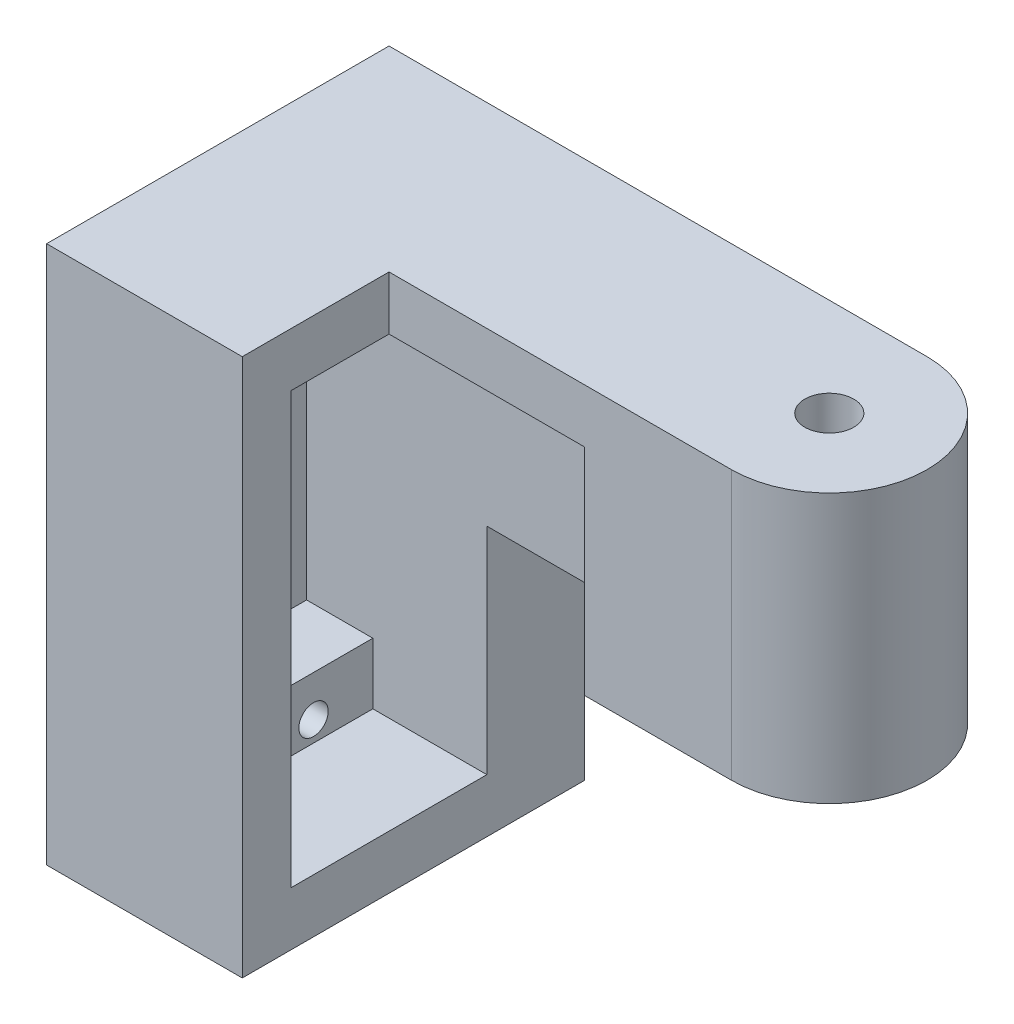
SolidWorks part; units mm, degrees
ref_plane "Front Plane" through (0, 0, 0) normal (0, 0, 1) x (1, 0, 0)
ref_plane "Top Plane" through (0, 0, 0) normal (0, 1, 0) x (1, 0, 0)
ref_plane "Right Plane" through (0, 0, 0) normal (1, 0, 0) x (0, 0, -1)
sketch "Sketch1" plane through (0, 0, 0) normal (0, 0, 1) x (1, 0, 0)
  line L1 (-76.2, -19.05) -> (76.2, -19.05)
  line L2 (-76.2, -19.05) -> (-76.2, 19.05)
  line L3 (-76.2, 19.05) -> (76.2, 19.05)
  line L4 (76.2, -19.05) -> (76.2, 19.05)
  line L5 (-76.2, -19.05) -> (76.2, 19.05) construction
  line L6 (-76.2, 19.05) -> (76.2, -19.05) construction
  circle A1 centre (76.2, 0) radius 19.05
  point P0 (0, 0)
  dimension "D1" = 38.1
  dimension "D2" = 152.4
extrude "Boss-Extrude1" add sketch "Sketch1" along normal blind 25.4
sketch "Sketch4" plane through (0, 0, 25.4) normal (0, 0, 1) x (1, 0, 0)
  line L1 (-76.2, 45.72) -> (-50.8, 45.72)
  line L2 (-76.2, 45.72) -> (-76.2, -24.13)
  line L3 (-76.2, -24.13) -> (-50.8, -24.13)
  line L4 (-50.8, 45.72) -> (-50.8, -24.13)
  line L5 (-76.2, 0) -> (95.25, 0) construction
  line L6 (-76.2, -19.05) -> (-76.2, 19.05) construction
  line L8 (-76.2, -19.05) -> (76.2, -19.05) construction
  arc A0 (76.2, -19.05) -> (76.2, 19.05) centre (76.2, 0) ccw construction
  point P10 (-71.4875, 31.0279)
  point P13 (-76.2, -21.835)
  dimension "D1" = 25.4
  dimension "D2" = 69.85
  dimension "D3" = 5.08
extrude "Boss-Extrude3" add sketch "Sketch4" along normal blind 19.05 and the other way up to surface other way up to face at (4.7625, 0, 0)
sketch "Sketch5" plane through (-76.2, 0, 0) normal (-1, 0, 0) x (0, 0, 1)
  line L0 (32.385, 0) -> (18.415, 0) construction
  line L1 (30.4, 34.4998) -> (20.4, 34.4998) construction
  line L2 (30.4, -14.5001) -> (20.4, -14.5001) construction
  line L3 (25.4, 6.985) -> (25.4, -6.985) construction
  line L10 (25.4, -19.05) -> (25.4, 19.05) construction
  circle A0 centre (25.4, 0) radius 6.985
  circle A1 centre (30.4, -14.5001) radius 1.905
  circle A2 centre (30.4, 34.4998) radius 1.905
  circle A3 centre (20.4, 34.4998) radius 1.905
  circle A4 centre (20.4, -14.5001) radius 1.905
  point P2 (36.4462, -5.8241)
  point P3 (30.6052, -14.5696)
  point P4 (32.385, 0)
  point P19 (25.4, 0)
  dimension "D1" = 13.97
  dimension "D2" = 3.81
  dimension "D3" = 48.9999
  dimension "D4" = 14.5001
  dimension "D5" = 10
extrude "Cut-Extrude1" cut sketch "Sketch5" against normal up to surface (25.4 mm away) up to face at (-50.8, 5.3975, 17.4625)
sketch "Sketch13" plane through (0, 0, 25.4) normal (0, 0, 1) x (1, 0, 0)
  line L0 (-76.2, -24.13) -> (-50.8, -24.13) construction
  line L1 (-50.8, 45.72) -> (12.7, 45.72)
  line L2 (-50.8, 45.72) -> (-50.8, -24.13)
  line L3 (-50.8, -24.13) -> (12.7, -24.13)
  line L4 (12.7, 45.72) -> (12.7, -24.13)
  dimension "D1" = 63.5
extrude "Boss-Extrude6" add sketch "Sketch13" against normal up to surface (25.4 mm away) up to face at (-23.0188, 5.3975, 0)
sketch "Sketch7" plane through (0, 0, 25.4) normal (0, 0, 1) x (1, 0, 0)
  line L0 (-50.8, -24.13) -> (12.7, -24.13) construction
  line L2 (-50.8, 6.985) -> (-50.8, 45.72) construction
  line L3 (0, -17.145) -> (-50.8, -17.145)
  line L4 (0, -17.145) -> (0, 38.735)
  line L5 (0, 38.735) -> (-50.8, 38.735)
  line L6 (-50.8, -17.145) -> (-50.8, 38.735)
  line L7 (0, -17.145) -> (-50.8, 38.735) construction
  line L8 (0, 38.735) -> (-50.8, -17.145) construction
  line L9 (0, -17.145) -> (0, -24.13) construction
  line L12 (0, 38.735) -> (0, 45.72) construction
  line L15 (12.7, 45.72) -> (-50.8, 45.72) construction
  point P0 (0, -21.59)
  point P2 (0, 41.91)
  point P5 (-25.4, 10.795)
  point P15 (0, -41.91)
  dimension "D1" = 55.88
  dimension "D2" = 50.8
extrude "Cut-Extrude2" cut sketch "Sketch7" against normal up to surface (25.4 mm away) up to face at (8.7312, 5.3975, 0)
sketch "Sketch8" plane through (-50.8, 0, 0) normal (1, 0, 0) x (0, 0, -1)
  line L1 (-38.1, -9.205) -> (-12.7, -9.205)
  line L2 (-38.1, -9.205) -> (-38.1, 30.795)
  line L3 (-38.1, 30.795) -> (-12.7, 30.795)
  line L4 (-12.7, -9.205) -> (-12.7, 30.795)
  line L5 (-38.1, -9.205) -> (-12.7, 30.795) construction
  line L6 (-38.1, 30.795) -> (-12.7, -9.205) construction
  line L11 (-25.4, 30.795) -> (-25.4, -9.205) construction
  line L12 (-25.4, -24.13) -> (-25.4, -17.145) construction
  line L13 (-38.1, 10.795) -> (-12.7, 10.795) construction
  line L14 (-44.45, 10.795) -> (0, 10.795) construction
  line L15 (-44.45, -24.13) -> (-44.45, 45.72) construction
  line L16 (0, -17.145) -> (0, 38.735) construction
  point P0 (-25.4, 10.795)
  point P5 (-10.16, 30.3259)
  dimension "D1" = 25.4
  dimension "D2" = 39.9999
extrude "Cut-Extrude3" cut sketch "Sketch8" against normal offset from surface (23.4 mm away) 2 up to face at (-76.2, -14.5001, 18.495)
sketch "Sketch9" plane through (-50.8, 0, 0) normal (1, 0, 0) x (0, 0, -1)
  line L0 (-25.4, 30.795) -> (-25.4, -9.205) construction
  line L1 (-12.7, 30.795) -> (-38.1, 30.795) construction
  line L2 (-38.1, -9.205) -> (-12.7, -9.205) construction
  line L8 (-38.1, 30.795) -> (-12.7, 30.795)
  line L9 (-12.7, 38.735) -> (-12.7, 30.795)
  line L10 (-38.1, 38.735) -> (-12.7, 38.735)
  line L11 (-38.1, 38.735) -> (-38.1, 30.795)
  line L12 (0, 38.735) -> (-25.4, 38.735) construction
  line L13 (-38.1, 10.795) -> (-12.7, 10.795) construction
  line L14 (-38.1, 30.795) -> (-38.1, -9.205) construction
  line L15 (-12.7, -9.205) -> (-12.7, 30.795) construction
  line L16 (-38.1, -17.145) -> (-38.1, -9.205)
  line L17 (-38.1, -17.145) -> (-12.7, -17.145)
  line L18 (-12.7, -17.145) -> (-12.7, -9.205)
  line L19 (-38.1, -9.205) -> (-12.7, -9.205)
extrude "Cut-Extrude4" cut sketch "Sketch9" against normal offset from surface (14.8001 mm away) 10.5999 up to face at (-76.2, -14.5001, 18.495)
sketch "Sketch10" plane through (-65.6001, 0, 0) normal (1, 0, 0) x (0, 0, -1)
  line L0 (-25.4, -9.205) -> (-25.4, 30.795) construction
  line L1 (-38.1, 10.795) -> (-12.7, 10.795) construction
  line L2 (-38.1, 38.735) -> (-38.1, -17.145) construction
  line L3 (-38.1, 10.795) -> (-12.7, 10.795) construction
  line L4 (-38.1, -17.145) -> (-12.7, -17.145) construction
  line L5 (-12.7, -17.145) -> (-12.7, 38.735) construction
  line L6 (-38.1, -9.205) -> (-12.7, -9.205) construction
  line L7 (-26.67, -17.145) -> (-26.67, -9.205)
  line L8 (-26.67, -17.145) -> (-24.13, -17.145)
  line L9 (-24.13, -17.145) -> (-24.13, -9.205)
  line L10 (-26.67, -9.205) -> (-24.13, -9.205)
  line L11 (-26.67, -17.145) -> (-24.13, -9.205) construction
  line L12 (-24.13, -17.145) -> (-26.67, -9.205) construction
  line L14 (-24.13, 38.735) -> (-24.13, 30.795)
  line L15 (-26.67, 30.795) -> (-24.13, 30.795)
  line L16 (-26.67, 38.735) -> (-26.67, 30.795)
  line L17 (-26.67, 38.735) -> (-24.13, 38.735)
  line L18 (-25.4, 30.795) -> (-25.4, -9.205) construction
  line L19 (-38.1, 30.795) -> (-12.7, 30.795) construction
  line L20 (-12.7, -9.205) -> (-38.1, -9.205) construction
  point P0 (-27.0013, -4.7743)
  point P1 (-25.1485, -9.205)
  point P2 (-18.1321, 18.8615)
  point P6 (-24.9006, 30.795)
  point P7 (0, 0)
  point P8 (0, 0)
  point P12 (-25.4, -13.175)
  dimension "D1" = 2.54
extrude "Cut-Extrude5" cut sketch "Sketch10" against normal up to surface (8.5999 mm away) up to face at (-74.2, 10.795, 25.4)
sketch "Sketch11" plane through (0, 0, 25.4) normal (0, 0, 1) x (1, 0, 0)
  circle A0 centre (76.2, 0) radius 3.175
  arc A1 (76.2, -19.05) -> (76.2, 19.05) centre (76.2, 0) ccw construction
  dimension "D1" = 6.35
extrude "Cut-Extrude6" cut sketch "Sketch11" against normal through all
sketch "Sketch14" plane through (0, -17.145, 0) normal (0, 1, 0) x (1, 0, 0)
  line L0 (-50.8, -12.7) -> (-25.4, -12.7)
  line L1 (-25.4, -12.7) -> (-25.4, -25.4)
  line L2 (-50.8, -25.4) -> (0, -25.4) construction
  line L3 (-25.4, -25.4) -> (0, -25.4)
  line L4 (0, -25.4) -> (0, 0)
  line L5 (0, 0) -> (-50.8, 0)
  line L6 (-50.8, 0) -> (-50.8, -12.7)
  dimension "D1" = 25.4
extrude "Boss-Extrude7" add sketch "Sketch14" along normal up to surface (55.88 mm away) contours L6 L0 L1 L3 L4 L5 up to face at (-51.1667, 38.735, 21.1667)
sketch "Sketch15" plane through (0, 45.72, 0) normal (0, 1, 0) x (1, 0, 0)
  line L0 (12.7, -25.4) -> (-50.8, -25.4) construction
  line L1 (-76.2, 0) -> (12.7, 0) construction
  line L2 (-6.35, 0) -> (95.25, 0)
  line L3 (95.25, 0) -> (95.25, -25.4)
  line L4 (95.25, -25.4) -> (-6.35, -25.4)
  line L5 (-25.4, -12.7) -> (-25.4, -25.4) construction
  arc A0 (-6.35, -25.4) -> (-6.35, 0) centre (-6.35, -12.7) ccw
  dimension "D1" = 19.05
extrude "Cut-Extrude7" cut sketch "Sketch15" against normal through all
sketch "Sketch16" plane through (0, 0, 25.4) normal (0, 0, 1) x (1, 0, 0)
  line L0 (6.35, -24.13) -> (6.35, 45.72) construction
  line L1 (-50.8, -24.13) -> (6.35, -24.13)
  line L2 (-50.8, -24.13) -> (-50.8, 10.795)
  line L3 (-50.8, 10.795) -> (6.35, 10.795)
  line L4 (6.35, -24.13) -> (6.35, 10.795)
  line L5 (-50.8, 10.795) -> (6.35, 10.795) construction
  line L6 (-50.8, -24.13) -> (-50.8, 45.72) construction
extrude "Cut-Extrude8" cut sketch "Sketch16" against normal through all
sketch "Sketch17" plane through (0, 10.795, 0) normal (0, -1, 0) x (1, 0, 0)
  circle A0 centre (-6.35, 12.7) radius 3.175
  arc A1 (-6.35, 0) -> (-6.35, 25.4) centre (-6.35, 12.7) ccw construction
  point P2 (0, 0)
  dimension "D1" = 6.35
extrude "Cut-Extrude9" cut sketch "Sketch17" against normal through all
